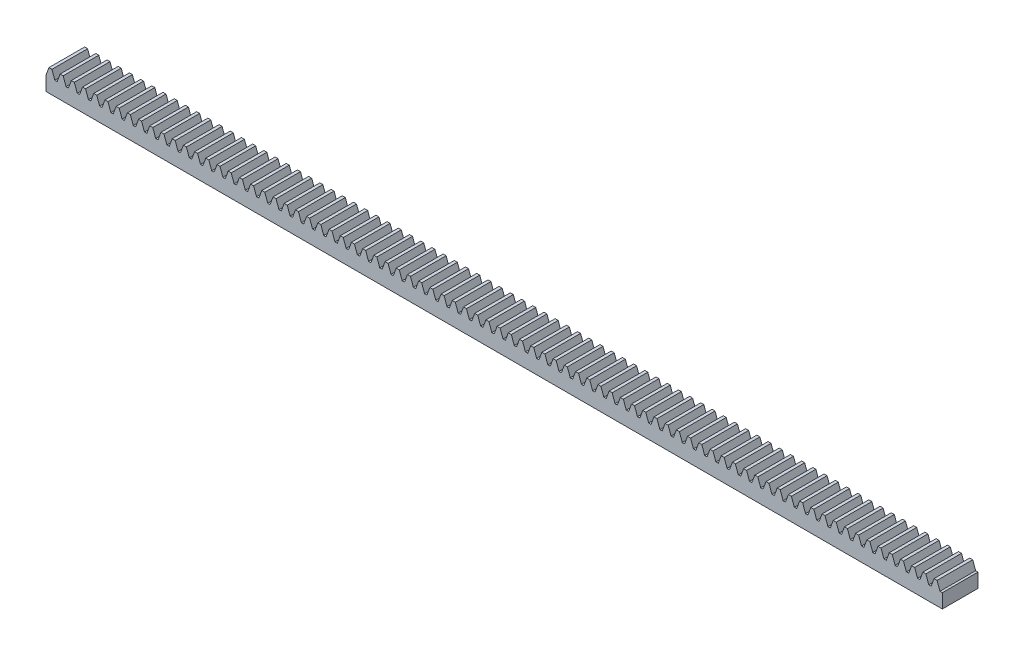
SolidWorks part; units mm, degrees
ref_plane "前视基准面" through (0, 0, 0) normal (0, 0, 1) x (1, 0, 0)
ref_plane "上视基准面" through (0, 0, 0) normal (0, 1, 0) x (1, 0, 0)
ref_plane "右视基准面" through (0, 0, 0) normal (1, 0, 0) x (0, 0, -1)
sketch "草图1" plane through (0, 0, 0) normal (0, 0, 1) x (1, 0, 0)
  line L1 (0, 0) -> (502.6548, 0)
  line L2 (0, 0) -> (0, -7.95)
  line L3 (0, -7.95) -> (502.6548, -7.95)
  line L4 (502.6548, 0) -> (502.6548, -7.95)
  dimension "D1" = 7.95
  dimension "L" = 502.6548
extrude "拉伸1" add sketch "草图1" along normal blind 20
sketch "草图2" plane through (0, 0, 20) normal (0, 0, 1) x (1, 0, 0)
  line L0 (0, 0) -> (1.6379, 4.5)
  line L1 (1.6379, 4.5) -> (3.3236, 4.5)
  line L2 (3.3236, 4.5) -> (4.9614, 0)
  line L3 (502.6548, 0) -> (0, 0) construction
  line L4 (0, 0) -> (4.9614, 0)
  line L5 (0.9099, 2.5) -> (4.0515, 2.5) construction
  dimension "D2" = 70
  dimension "alpha" = 110
  dimension "ha" = 2
  dimension "hf" = 2.5
  dimension "S" = 3.1416
extrude "拉伸2" add sketch "草图2" against normal up to surface (20 mm away) up to face at (251.3274, -3.975, 0)
pattern_linear "阵列(线性)1" count 80 spacing 6.2832 along (1, 0, 0) of "拉伸2"
equation "\"d\"=\"S@草图2\" * 2"
equation "\"z\"= int(  \"L@草图1\" / (  \"S@草图2\" * 2 ) + 0.5 )"
